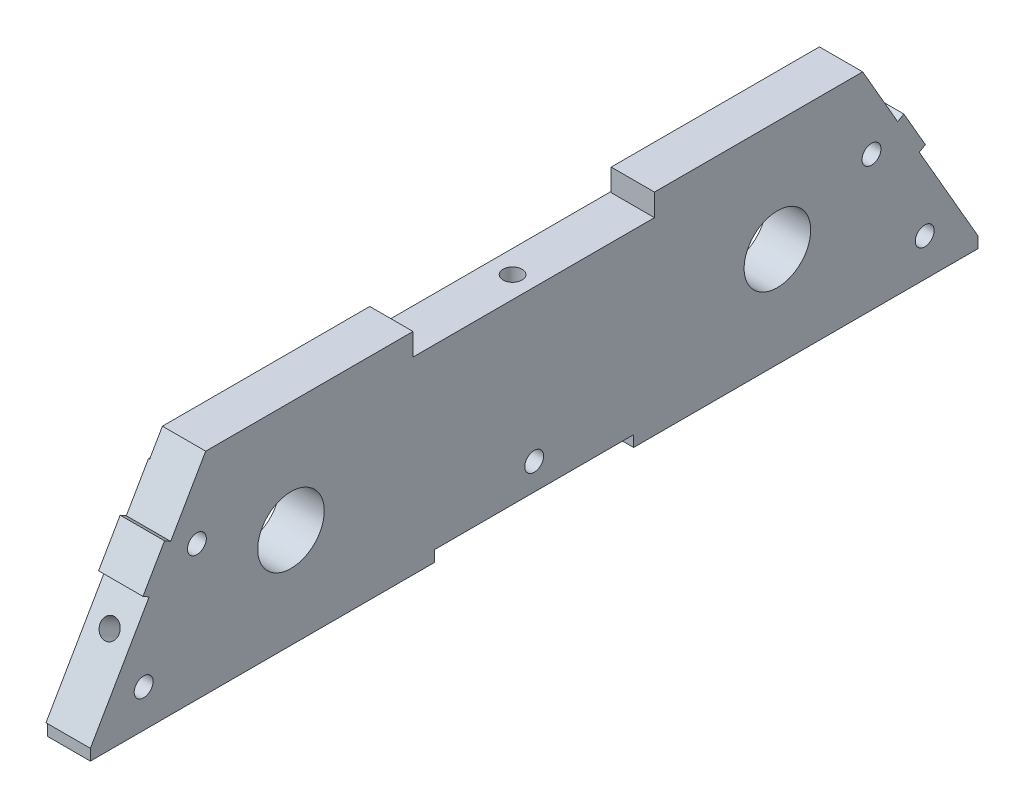
SolidWorks part; units mm, degrees
material "6061-T6 (SS)"
ref_plane "Front Plane" through (0, 0, 0) normal (0, 0, 1) x (1, 0, 0)
ref_plane "Top Plane" through (0, 0, 0) normal (0, 1, 0) x (1, 0, 0)
ref_plane "Right Plane" through (0, 0, 0) normal (1, 0, 0) x (0, 0, -1)
sketch "Sketch1" plane through (0, 0, 0) normal (1, 0, 0) x (0, 0, -1)
  line L0 (0, 0) -> (-14.6647, 25.4)
  line L1 (0, 0) -> (-127, 0)
  line L2 (-63.5, 25.4) -> (-63.5, 0.0032) construction
  line L3 (-14.6647, 25.4) -> (-112.3353, 25.4)
  line L5 (-127, 0) -> (-112.3353, 25.4)
  circle A0 centre (-98.298, 12.7) radius 4.7625
  circle A1 centre (-28.702, 12.7) radius 4.7625
  dimension "D3" = 9.525
  dimension "D5" = 9.525
  dimension "D9" = 60
  dimension "D2" = 28.702
  dimension "D4" = 12.7
  dimension "D6" = 28.702
  dimension "D7" = 25.4
  dimension "D8" = 12.7
  dimension "D10" = 60
  dimension "D11" = 127
extrude "Boss-Extrude1" add sketch "Sketch1" along normal blind 6.35
sketch "Sketch7" plane through (0, 0, 0) normal (0, 0.5, -0.866) x (-1, 0, 0)
  line L1 (-6.35, 22.9794) -> (0, 22.9794)
  line L2 (-6.35, 22.9794) -> (-6.35, 16.8072)
  line L3 (-6.35, 16.8072) -> (0, 16.8072)
  line L4 (0, 22.9794) -> (0, 16.8072)
  dimension "D1" = 6.1722
extrude "Boss-Extrude2" add sketch "Sketch7" along normal blind 1.016
sketch "Sketch8" plane through (0, 54.9926, 95.25) normal (0, 0.5, 0.866) x (1, 0, 0)
  line L0 (0, -34.1706) -> (0, -63.5) construction
  line L1 (6.35, -34.1706) -> (6.35, -63.5) construction
  line L2 (0, -40.5206) -> (6.35, -40.5206)
  line L3 (0, -40.5206) -> (0, -46.6928)
  line L4 (0, -46.6928) -> (6.35, -46.6928)
  line L5 (6.35, -40.5206) -> (6.35, -46.6928)
  line L6 (6.35, -34.1706) -> (0, -34.1706) construction
  dimension "D1" = 6.1722
  dimension "D2" = 6.35
extrude "Boss-Extrude3" add sketch "Sketch8" along normal blind 1.016
hole_wizard "Tap Drill for #6-32 Tap1" positions "Sketch13" profile "Sketch12" hole size "#6-32" standard "ANSI Inch"
sketch "Sketch13" plane through (6.35, 0, 0) normal (1, 0, 0) x (0, 0, -1)
  point P0 (-111.761, 17.7361)
  point P2 (-15.239, 17.7361)
  point P13 (-119.38, 3.81)
  point P15 (-7.62, 3.81)
  point P21 (-63.5, 3.81)
sketch "Sketch12" plane through (6.35, 17.7361, 111.761) normal (0, 1, 0) x (0, 0, -1)
  line L0 (0, 0) -> (0, 7.1627)
  line L1 (0, 7.1627) -> (1.3525, 6.35)
  line L2 (1.3525, 6.35) -> (1.3525, 0)
  line L5 (1.3525, 0) -> (0, 0)
  line L10 (0, 7.1627) -> (-1.3525, 6.35) construction
  line L11 (0, -6.35) -> (0, 107.95) construction
  dimension "Hole Dia." = 2.7051
  dimension "Hole Depth" = 6.35
  dimension "Drill Angle" = 118
hole_wizard "Tap Drill for #6-32 Tap2" positions "Sketch15" profile "Sketch14" hole size "#6-32" standard "ANSI Inch"
sketch "Sketch15" plane through (0, 54.9926, 95.25) normal (0, 0.5, 0.866) x (1, 0, 0)
  line L2 (6.35, -34.1706) -> (0, -34.1706) construction
  line L3 (0, -46.6928) -> (0, -63.5) construction
  point P3 (3.175, -51.6331)
  dimension "D1" = 17.4625
  dimension "D2" = 3.175
sketch "Sketch14" plane through (3.175, 10.277, 121.0666) normal (1, 0, 0) x (0, -0.866, 0.5)
  line L0 (0, 0) -> (0, 7.1627)
  line L1 (0, 7.1627) -> (1.3525, 6.35)
  line L2 (1.3525, 6.35) -> (1.3525, 0)
  line L5 (1.3525, 0) -> (0, 0)
  line L10 (0, 7.1627) -> (-1.3525, 6.35) construction
  line L11 (0, -6.35) -> (0, 107.95) construction
  dimension "Hole Dia." = 2.7051
  dimension "Hole Depth" = 6.35
  dimension "Drill Angle" = 118
hole_wizard "Tap Drill for #6-32 Tap3" positions "Sketch17" profile "Sketch16" hole size "#6-32" standard "ANSI Inch"
sketch "Sketch17" plane through (0, 0, 0) normal (0, 0.5, -0.866) x (-1, 0, 0)
  line L0 (-6.35, 29.3294) -> (0, 29.3294) construction
  line L1 (-6.35, 0) -> (-6.35, 16.8072) construction
  point P0 (-3.175, 11.8669)
  dimension "D1" = 17.4625
  dimension "D2" = 3.175
sketch "Sketch16" plane through (3.175, 10.277, 5.9334) normal (1, 0, 0) x (0, 0.866, 0.5)
  line L0 (0, 0) -> (0, 7.1627)
  line L1 (0, 7.1627) -> (1.3525, 6.35)
  line L2 (1.3525, 6.35) -> (1.3525, 0)
  line L5 (1.3525, 0) -> (0, 0)
  line L10 (0, 7.1627) -> (-1.3525, 6.35) construction
  line L11 (0, -6.35) -> (0, 107.95) construction
  dimension "Hole Dia." = 2.7051
  dimension "Hole Depth" = 6.35
  dimension "Drill Angle" = 118
sketch "Sketch18" plane through (0, 0, 0) normal (-1, 0, 0) x (0, 0, 1)
  line L0 (14.6647, 25.4) -> (112.3353, 25.4) construction
  line L1 (36.6395, 20.6375) -> (90.3605, 20.6375)
  line L2 (36.6395, 20.6375) -> (36.6395, 7.9375)
  line L3 (36.6395, 7.9375) -> (90.3605, 7.9375)
  line L4 (90.3605, 20.6375) -> (90.3605, 7.9375)
  line L5 (127, 0) -> (0, 0) construction
  circle A0 centre (28.702, 12.7) radius 4.7625 construction
  circle A1 centre (98.298, 12.7) radius 4.7625 construction
  dimension "D1" = 7.9375
  dimension "D2" = 7.9375
  dimension "D3" = 4.7625
  dimension "D4" = 7.9375
extrude "Cut-Extrude1" cut sketch "Sketch18" against normal blind 3.175
fillet "Fillet1" radius 2.54 4 edges at (1.5875, 7.9375, 36.6395) (1.5875, 20.6375, 36.6395) (1.5875, 7.9375, 90.3605) (1.5875, 20.6375, 90.3605)
sketch "Sketch19" plane through (0, 25.4, 0) normal (0, 1, 0) x (1, 0, 0)
  line L0 (23.0187, -46.2906) -> (0.1587, -46.2906) construction
  line L1 (0.1587, -80.8346) -> (23.0187, -80.8346) construction
  line L2 (23.0187, -46.2906) -> (0.1587, -46.2906) construction
  line L3 (0.1587, -80.8346) -> (23.0187, -80.8346) construction
  line L5 (0.1587, -46.2906) -> (6.35, -46.2906)
  line L6 (0.1587, -46.2906) -> (0.1587, -14.6647)
  line L7 (0.1587, -14.6647) -> (6.35, -14.6647)
  line L8 (6.35, -46.2906) -> (6.35, -14.6647)
  line L9 (0.1587, -80.8346) -> (6.35, -80.8346)
  line L10 (0.1587, -80.8346) -> (0.1587, -112.3353)
  line L11 (0.1587, -112.3353) -> (6.35, -112.3353)
  line L12 (6.35, -80.8346) -> (6.35, -112.3353)
extrude "Boss-Extrude4" add sketch "Sketch19" along normal blind 3.175
sketch "Sketch20" plane through (6.35, 0, 0) normal (1, 0, 0) x (0, 0, -1)
  line L0 (-112.3353, 25.4) -> (-110.5022, 28.575)
  line L1 (-112.3353, 28.575) -> (-80.8346, 28.575) construction
  line L2 (-110.5022, 28.575) -> (-112.3353, 28.575)
  line L3 (-112.3353, 28.575) -> (-112.3353, 25.4)
  line L4 (-14.6647, 25.4) -> (-16.4978, 28.575)
  line L5 (-46.2906, 28.575) -> (-14.6647, 28.575) construction
  line L6 (-16.4978, 28.575) -> (-14.6647, 28.575)
  line L7 (-14.6647, 28.575) -> (-14.6647, 25.4)
extrude "Cut-Extrude2" cut sketch "Sketch20" against normal through all
hole_wizard "Tap Drill for #6-32 Tap4" positions "Sketch22" profile "Sketch21" hole size "#6-32" standard "ANSI Inch"
sketch "Sketch22" plane through (0, 25.4, 0) normal (0, 1, 0) x (1, 0, 0)
  point P0 (3.2544, -63.5)
sketch "Sketch21" plane through (3.2544, 25.4, 63.5) normal (1, 0, 0) x (0, 0, 1)
  line L0 (0, 0) -> (0, 10.9727)
  line L1 (0, 10.9727) -> (1.3525, 10.16)
  line L2 (1.3525, 10.16) -> (1.3525, 0)
  line L5 (1.3525, 0) -> (0, 0)
  line L10 (0, 10.9727) -> (-1.3526, 10.16) construction
  line L11 (0, -6.35) -> (0, 107.95) construction
  dimension "Hole Dia." = 2.7051
  dimension "Hole Depth" = 10.16
  dimension "Drill Angle" = 118
sketch "Sketch23" plane through (0, 0, 0) normal (0, -1, 0) x (1, 0, 0)
  line L0 (21.8599, 49.276) -> (0.2222, 49.276) construction
  line L1 (21.8599, 49.276) -> (0.2222, 49.276) construction
  line L2 (0.2222, 77.7875) -> (21.8599, 77.7875) construction
  line L3 (0.2222, 77.7875) -> (21.8599, 77.7875) construction
  line L4 (21.8599, 49.276) -> (0.2222, 49.276)
  line L6 (0.2222, 77.7875) -> (6.35, 77.7875)
  line L7 (0.2222, 77.7875) -> (0.2222, 127)
  line L8 (0.2222, 127) -> (6.35, 127)
  line L9 (6.35, 77.7875) -> (6.35, 127)
  line L10 (0.2222, 49.276) -> (6.35, 49.276)
  line L11 (0.2222, 49.276) -> (0.2222, 0)
  line L12 (0.2222, 0) -> (6.35, 0)
  line L13 (6.35, 49.276) -> (6.35, 0)
  line M2 (0, 0) -> (6.35, 0)
  line M3 (6.35, 0) -> (6.35, 127)
  line M4 (6.35, 127) -> (0, 127)
extrude "Boss-Extrude5" add sketch "Sketch23" along normal blind 1.5875 contours L7 L6 M3 M4 | L4 L11 M2 M3
equation "\"D8@Sketch1\"=\"D4@Sketch1\""
